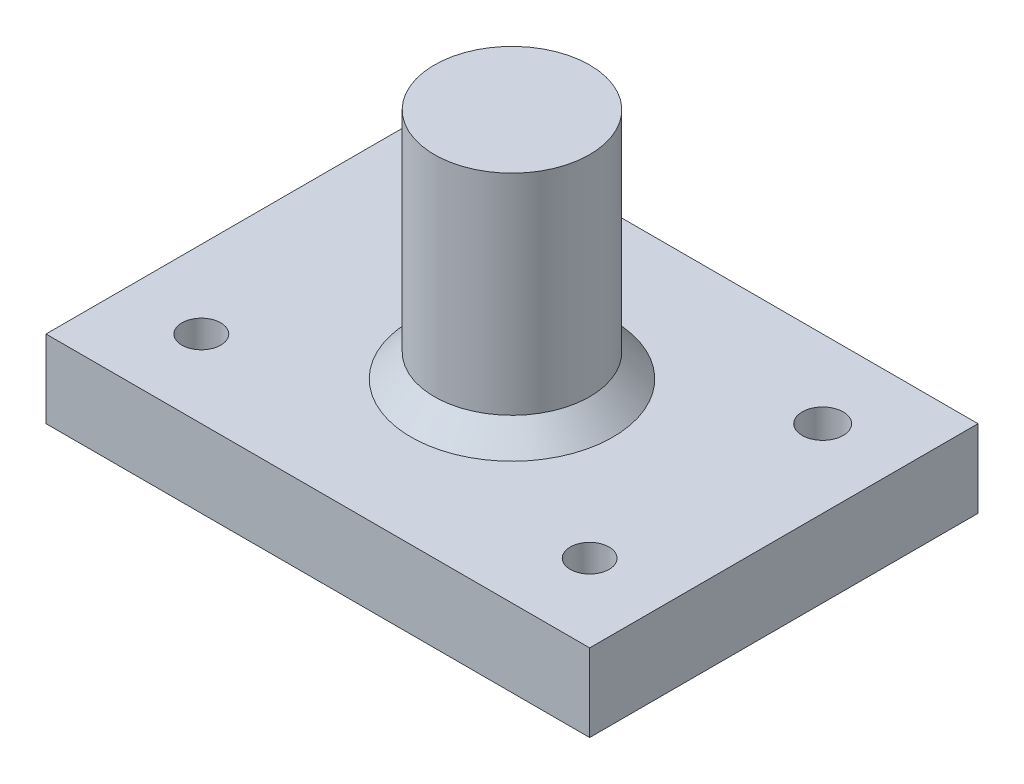
SolidWorks part; units mm, degrees
ref_plane "Front Plane" through (0, 0, 0) normal (0, 0, 1) x (1, 0, 0)
ref_plane "Top Plane" through (0, 0, 0) normal (0, 1, 0) x (1, 0, 0)
ref_plane "Right Plane" through (0, 0, 0) normal (1, 0, 0) x (0, 0, -1)
sketch "Sketch1" plane through (0, 0, 0) normal (0, 1, 0) x (1, 0, 0)
  line L0 (-31.75, 19.05) -> (-31.75, -19.05) construction
  line L1 (-44.45, -31.75) -> (44.45, -31.75)
  line L2 (-44.45, -31.75) -> (-44.45, 31.75)
  line L3 (-44.45, 31.75) -> (44.45, 31.75)
  line L4 (44.45, -31.75) -> (44.45, 31.75)
  line L5 (-44.45, -31.75) -> (44.45, 31.75) construction
  line L6 (-44.45, 31.75) -> (44.45, -31.75) construction
  line L7 (-31.75, -19.05) -> (31.75, -19.05) construction
  line L8 (31.75, -19.05) -> (31.75, 19.05) construction
  line L9 (31.75, 19.05) -> (-31.75, 19.05) construction
  line L10 (-31.75, 19.05) -> (31.75, -19.05) construction
  line L11 (31.75, 19.05) -> (-31.75, -19.05) construction
  circle A0 centre (-31.75, 19.05) radius 3.175
  circle A1 centre (-31.75, -19.05) radius 3.175
  circle A2 centre (31.75, -19.05) radius 3.175
  circle A3 centre (31.75, 19.05) radius 3.3492
  point P0 (0, 0)
  point P11 (0, 0)
  dimension "D3" = 6.35
  dimension "D1" = 63.5
  dimension "D2" = 88.9
  dimension "D4" = 63.5
  dimension "D5" = 38.1
extrude "Boss-Extrude1" add sketch "Sketch1" along normal blind 12.7
sketch "Sketch2" plane through (0, 12.7, 0) normal (0, 1, 0) x (1, 0, 0)
  circle A0 centre (0, 0) radius 12.7
  dimension "D1" = 25.4
extrude "Boss-Extrude2" add sketch "Sketch2" along normal blind 38.1
chamfer "Chamfer1" distance 3.81 angle 45 1 edges at (0, 12.7, 12.7)
